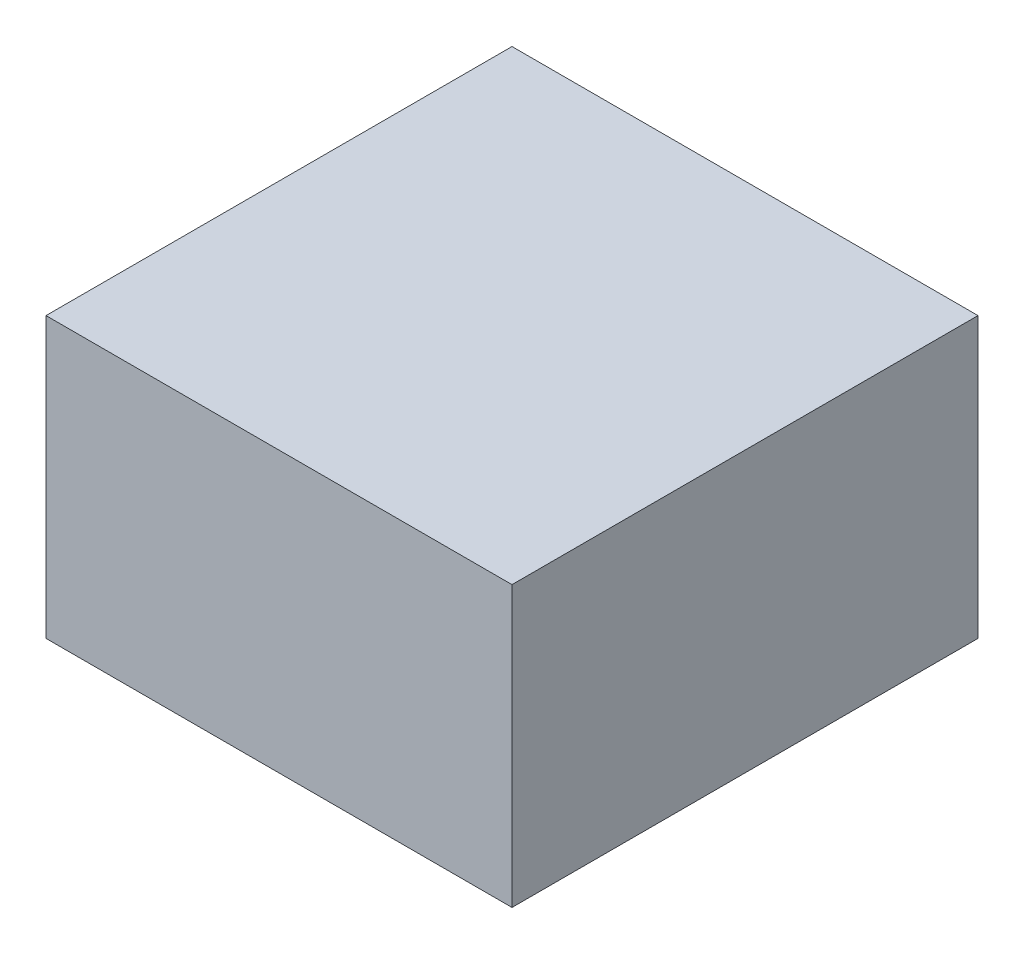
SolidWorks part; units mm, degrees
ref_plane "Front Plane" through (0, 0, 0) normal (0, 0, 1) x (1, 0, 0)
ref_plane "Top Plane" through (0, 0, 0) normal (0, 1, 0) x (1, 0, 0)
ref_plane "Right Plane" through (0, 0, 0) normal (1, 0, 0) x (0, 0, -1)
sketch "Sketch1" plane through (0, 0, 0) normal (0, 1, 0) x (1, 0, 0)
  line L1 (-31.75, -31.75) -> (31.75, -31.75)
  line L2 (-31.75, -31.75) -> (-31.75, 31.75)
  line L3 (-31.75, 31.75) -> (31.75, 31.75)
  line L4 (31.75, -31.75) -> (31.75, 31.75)
  line L5 (-31.75, -31.75) -> (31.75, 31.75) construction
  line L6 (-31.75, 31.75) -> (31.75, -31.75) construction
  point P0 (0, 0)
  dimension "D1" = 63.5
  dimension "D2" = 63.5
extrude "Boss-Extrude1" add sketch "Sketch1" along normal blind 38.1
